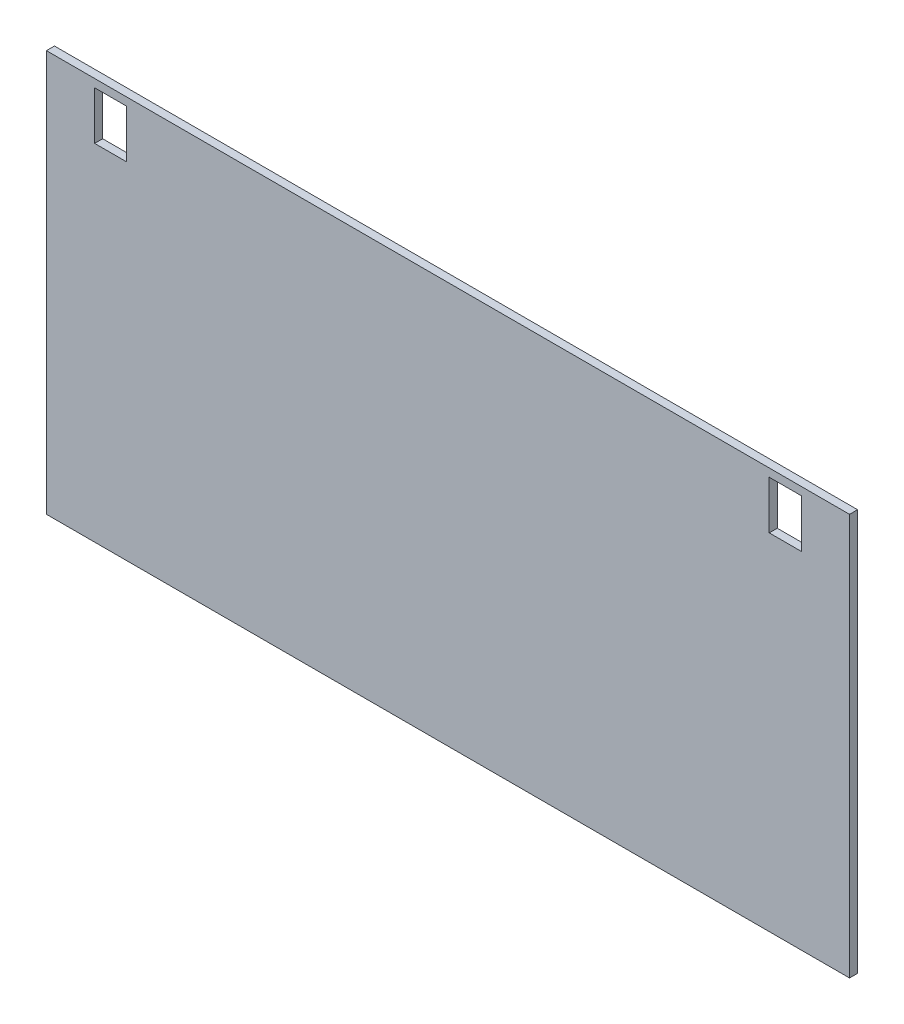
SolidWorks part; units mm, degrees
ref_plane "前基準面" through (0, 0, 0) normal (0, 0, 1) x (1, 0, 0)
ref_plane "上基準面" through (0, 0, 0) normal (0, 1, 0) x (1, 0, 0)
ref_plane "右基準面" through (0, 0, 0) normal (1, 0, 0) x (0, 0, -1)
sketch "草圖1" plane through (0, 0, 0) normal (0, 0, 1) x (1, 0, 0)
  line L0 (-40, 18) -> (40, 18) construction
  line L1 (-50, 25) -> (50, 25)
  line L2 (-50, 25) -> (-50, -25)
  line L3 (-50, -25) -> (50, -25)
  line L4 (50, 25) -> (50, -25)
  line L5 (-44, 24) -> (-40, 24)
  line L6 (-44, 24) -> (-44, 18)
  line L7 (-44, 18) -> (-40, 18)
  line L8 (-40, 24) -> (-40, 18)
  line L9 (40, 24) -> (44, 24)
  line L10 (40, 24) -> (40, 18)
  line L11 (40, 18) -> (44, 18)
  line L12 (44, 24) -> (44, 18)
  point P4 (0, 25)
  point P5 (-50, 0)
  point P15 (0, 18)
  dimension "D1" = 100
  dimension "D2" = 50
  dimension "D3" = 6
  dimension "D4" = 1
  dimension "D5" = 4
  dimension "D6" = 80
extrude "填料-伸長1" add sketch "草圖1" along normal mid plane 1 contours L1 L4 L3 L2
